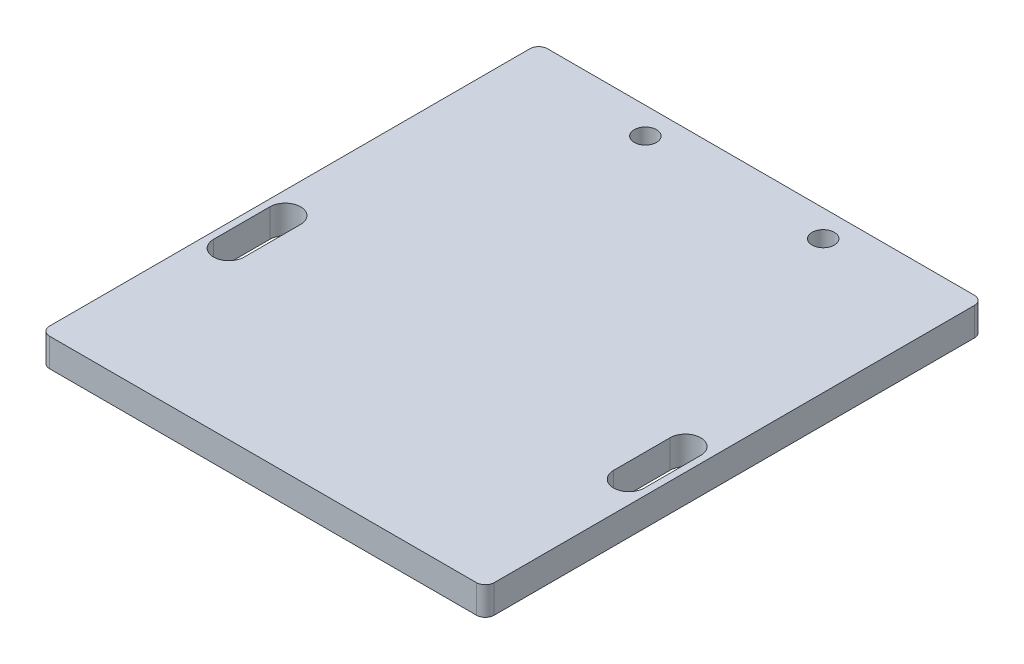
SolidWorks part; units mm, degrees
ref_plane "Front Plane" through (0, 0, 0) normal (0, 0, 1) x (1, 0, 0)
ref_plane "Top Plane" through (0, 0, 0) normal (0, 1, 0) x (1, 0, 0)
ref_plane "Right Plane" through (0, 0, 0) normal (1, 0, 0) x (0, 0, -1)
sketch "Sketch1" plane through (0, 0, 0) normal (0, 1, 0) x (1, 0, 0)
  line L1 (0, 0) -> (50, 0)
  line L2 (0, 0) -> (0, -56)
  line L3 (0, -56) -> (50, -56)
  line L4 (50, 0) -> (50, -56)
  circle A0 centre (15, -3) radius 1.1
  circle A1 centre (35, -3) radius 1.1
  dimension "D4" = 2.2
  dimension "D1" = 56
  dimension "D2" = 20
  dimension "D5" = 50
  dimension "D6" = 15
  dimension "D3" = 3
extrude "Boss-Extrude1" add sketch "Sketch1" along normal blind 3.175
fillet "Fillet1" radius 1 4 edges at (0, 1.5875, 56) (50, 1.5875, 56) (50, 1.5875, 0) (0, 1.5875, 0)
hole_wizard "M3x0.5 Tapped Hole1" positions "3DSketch1" profile "Sketch2" tap size "M3x0.5" standard "ANSI Metric" end condition through all
sketch3d "3DSketch1"
  circle A0 centre (35, 3.175, 3) radius 1.1 construction
  circle A1 centre (15, 3.175, 3) radius 1.1 construction
  point P0 (15, 3.175, 3)
  point P2 (35, 3.175, 3)
  point P7 (35, 4.275, 3)
  point P11 (15, 4.275, 3)
sketch "Sketch2" plane through (15, 3.175, 3) normal (1, 0, 0) x (0, 0, 1)
  line L0 (0, 0) -> (0, 3.175)
  line L1 (0, 3.175) -> (1.25, 3.175)
  line L2 (1.25, 3.175) -> (1.25, 0)
  line L5 (1.25, 0) -> (0, 0)
  line L11 (0, -6.35) -> (0, 107.95) construction
  dimension "Thru Tap Drill Dia." = 2.5
  dimension "Thru Tap Drill Depth" = 3.175
cosmetic thread "Hole Thread1" parameters "D2"=3
cosmetic thread "Hole Thread2" parameters "D2"=3
sketch "Sketch3" plane through (0, 3.175, 0) normal (0, 1, 0) x (1, 0, 0)
  line L0 (2.5, -31) -> (47.5, -31) construction
  line L1 (0, -1) -> (0, -55) construction
  line L2 (50, -55) -> (50, -1) construction
  line L3 (1, -56) -> (49, -56) construction
  line L4 (2.5, -31) -> (2.5, -37.35) construction
  line L5 (4.225, -31) -> (4.225, -37.35)
  line L6 (0.775, -31) -> (0.775, -37.35)
  line L7 (47.5, -31) -> (47.5, -37.35) construction
  line L8 (49.225, -31) -> (49.225, -37.35)
  line L9 (45.775, -31) -> (45.775, -37.35)
  arc A0 (4.225, -31) -> (0.775, -31) centre (2.5, -31) ccw
  arc A1 (49.225, -31) -> (45.775, -31) centre (47.5, -31) ccw
  arc A2 (4.225, -31) -> (0.775, -31) centre (2.5, -31) ccw
  arc A3 (0.775, -37.35) -> (4.225, -37.35) centre (2.5, -37.35) ccw
  arc A4 (49.225, -31) -> (45.775, -31) centre (47.5, -31) ccw
  arc A5 (45.775, -37.35) -> (49.225, -37.35) centre (47.5, -37.35) ccw
  point P10 (2.5, -34.175)
  point P16 (47.5, -34.175)
  point P22 (2.5, -36.4242)
  point P23 (0, 0)
  point P24 (4.225, -36.3224)
  dimension "D1" = 3.45
  dimension "D2" = 2.5
  dimension "D3" = 2.5
  dimension "D4" = 25
  dimension "D5" = 45
  dimension "D6" = 6.35
extrude "Cut-Extrude1" cut sketch "Sketch3" against normal through all both contours L6 A3 L5 A0 | L9 A5 L8 A1
equation "\"D6@Sketch1\"=(\"D5@Sketch1\"-\"D2@Sketch1\")/2"
equation "\"D3@Sketch3\"=\"D2@Sketch3\""
